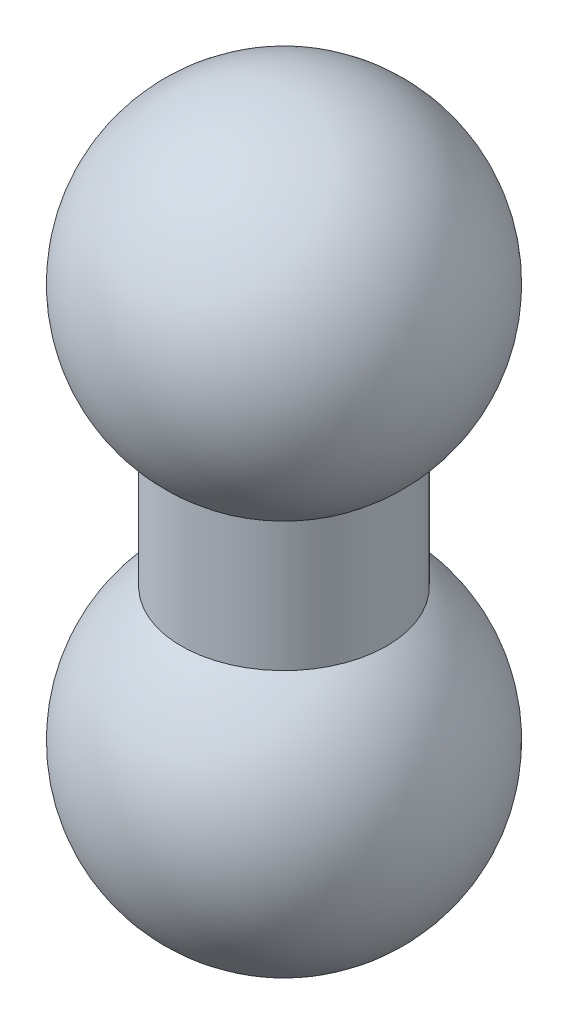
SolidWorks part; units mm, degrees
ref_plane "Front Plane" through (0, 0, 0) normal (0, 0, 1) x (1, 0, 0)
ref_plane "Top Plane" through (0, 0, 0) normal (0, 1, 0) x (1, 0, 0)
ref_plane "Right Plane" through (0, 0, 0) normal (1, 0, 0) x (0, 0, -1)
sketch "Sketch1" plane through (0, 0, 0) normal (0, 0, 1) x (1, 0, 0)
  line L4 (10.6595, 9.6115) -> (10.6595, -9.6115)
  line L5 (0, 0) -> (10.6595, -25.4) construction
  line L6 (0, 0) -> (10.6595, 25.4) construction
  line L7 (0, 50.0103) -> (0, -50.8746) construction
  arc A0 (0, 6.35) -> (2.7485, 6.5493) centre (0, 25.4) ccw
  arc A1 (0, -44.45) -> (10.6595, -9.6115) centre (0, -25.4) ccw
  arc A2 (10.6595, 9.6115) -> (0, 44.45) centre (0, 25.4) ccw
  arc A3 (2.7485, -6.5493) -> (0, -6.35) centre (0, -25.4) ccw
  point P0 (0, 0)
  dimension "D1" = 38.1
  dimension "D2" = 38.1
revolve "Revolve-Thin2" add sketch "Sketch1" angle 360 about L7
